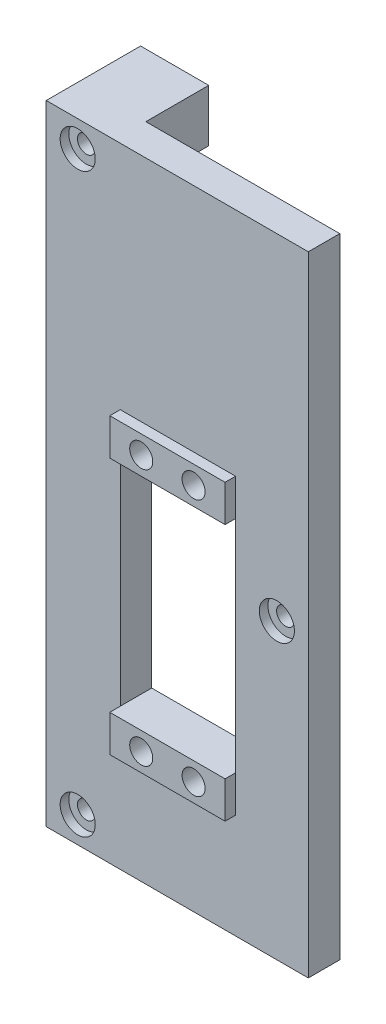
SolidWorks part; units mm, degrees
ref_plane "Front Plane" through (0, 0, 0) normal (1, 0, 0) x (0, 1, 0)
ref_plane "Top Plane" through (0, 0, 0) normal (0, 0, 1) x (0, 1, 0)
ref_plane "Right Plane" through (0, 0, 0) normal (0, 1, 0) x (-1, 0, 0)
sketch "Sketch1" plane through (0, 0, 0) normal (0, 0, 1) x (0, 1, 0)
  line L1 (60, -25) -> (-60, -25)
  line L2 (60, -25) -> (60, 25)
  line L3 (60, 25) -> (-60, 25)
  line L4 (-60, -25) -> (-60, 25)
  line L5 (60, -25) -> (-60, 25) construction
  line L6 (60, 25) -> (-60, -25) construction
  point P0 (0, 0)
  dimension "D1" = 120
  dimension "D2" = 50
extrude "Boss-Extrude1" add sketch "Sketch1" along normal blind 6
sketch "Sketch2" plane through (0, 0, 0) normal (0, 0, -1) x (1, 0, 0)
  line L0 (25, 60) -> (25, -60) construction
  line L1 (-25, 60) -> (25, 60)
  line L2 (-25, 60) -> (-25, 50)
  line L3 (-25, 50) -> (25, 50)
  line L4 (25, 60) -> (25, 50)
  line L5 (25, 0) -> (-25, 0) construction
  line L6 (-25, -60) -> (-25, 60) construction
  line L7 (25, -60) -> (25, -50)
  line L8 (-25, -50) -> (25, -50)
  line L9 (-25, -60) -> (-25, -50)
  line L10 (-25, -60) -> (25, -60)
  point P13 (0, 0)
  dimension "D1" = 10
extrude "Boss-Extrude2" add sketch "Sketch2" along normal blind 12
sketch "Sketch3" plane through (0, 0, 6) normal (0, 0, 1) x (1, 0, 0)
  line L0 (25, 0) -> (-25, 0) construction
  line L1 (-25, 60) -> (-25, -60) construction
  line L2 (-25, -60) -> (25, -60) construction
  circle A0 centre (-19, -55) radius 1.7
  circle A3 centre (-19, 55) radius 1.7
  point P10 (0, 0)
  dimension "D1" = 3.4
  dimension "D3" = 6
  dimension "D5" = 5
extrude "Cut-Extrude1" cut sketch "Sketch3" against normal blind 19
sketch "Sketch5" plane through (25, 0, 0) normal (1, 0, 0) x (0, 1, 0)
  line L0 (0, 0) -> (0, -11.428) construction
  line L2 (-50, 0) -> (-60, 0)
  line L3 (-50, 0) -> (-50, -12)
  line L4 (-50, -12) -> (-60, -12)
  line L5 (-60, 0) -> (-60, -12)
  line L6 (50, 0) -> (60, 0)
  line L7 (50, 0) -> (50, -12)
  line L8 (50, -12) -> (60, -12)
  line L9 (60, 0) -> (60, -12)
extrude "Cut-Extrude2" cut sketch "Sketch5" against normal blind 37
sketch "Sketch6" plane through (0, 0, 0) normal (0, 0, -1) x (1, 0, 0)
  line L0 (25, 60) -> (25, -60) construction
  line L1 (-12, 60) -> (25, 60) construction
  circle A0 centre (19, 4) radius 1.7
  dimension "D1" = 3.4
  dimension "D2" = 6
  dimension "D3" = 56
hole_wizard "CBORE for M3 SBHCS2" positions "3DSketch2" profile "Sketch7" counterbore size "M3" standard "ANSI Metric"
sketch3d "3DSketch2"
  line L0 (-19, 55, -12) -> (-19, 55, 6) construction
  line L1 (-19, -55, -12) -> (-19, -55, 6) construction
  point P0 (-19, 55, 6)
  point P4 (-19, -55, 6)
sketch "Sketch7" plane through (-19, 55, 6) normal (1, 0, 0) x (0, -1, 0)
  line L0 (0, 0) -> (0, 4.1715)
  line L1 (0, 4.1715) -> (1.7, 3.15)
  line L2 (1.7, 3.15) -> (1.7, 1.65)
  line L3 (1.7, 1.65) -> (3.35, 1.65)
  line L4 (3.35, 1.65) -> (3.35, 0)
  line L5 (3.35, 0) -> (0, 0)
  line L10 (0, 4.1715) -> (-1.7, 3.15) construction
  line L11 (0, -6.35) -> (0, 107.95) construction
  dimension "Hole Dia." = 3.4
  dimension "Hole Depth" = 3.15
  dimension "C'Bore Dia." = 6.7
  dimension "C'Bore Depth" = 1.65
  dimension "Drill Angle" = 118
extrude "Cut-Extrude3" cut sketch "Sketch6" against normal blind 6
hole_wizard "CBORE for M3 SBHCS3" positions "3DSketch3" profile "Sketch8" counterbore size "M3" standard "ANSI Metric"
sketch3d "3DSketch3"
  line L0 (19, -4, 6) -> (19, -4, 0) construction
  point P0 (19, -4, 6)
sketch "Sketch8" plane through (19, -4, 6) normal (1, 0, 0) x (0, -1, 0)
  line L0 (0, 0) -> (0, 4.1715)
  line L1 (0, 4.1715) -> (1.7, 3.15)
  line L2 (1.7, 3.15) -> (1.7, 1.65)
  line L3 (1.7, 1.65) -> (3.35, 1.65)
  line L4 (3.35, 1.65) -> (3.35, 0)
  line L5 (3.35, 0) -> (0, 0)
  line L10 (0, 4.1715) -> (-1.7, 3.15) construction
  line L11 (0, -6.35) -> (0, 107.95) construction
  dimension "Hole Dia." = 3.4
  dimension "Hole Depth" = 3.15
  dimension "C'Bore Dia." = 6.7
  dimension "C'Bore Depth" = 1.65
  dimension "Drill Angle" = 118
sketch "Sketch9" plane through (0, 0, 6) normal (0, 0, 1) x (1, 0, 0)
  line L0 (25, -60) -> (25, 60) construction
  line L1 (-25, -60) -> (25, -60) construction
  circle A0 centre (0.12, -22.03) radius 3.2
  dimension "D1" = 24.88
  dimension "D2" = 37.97
  dimension "D3" = 6.4
extrude "Cut-Extrude4" cut sketch "Sketch9" against normal blind 7
sketch "Sketch10" plane through (0, 0, 6) normal (0, 0, 1) x (1, 0, 0)
  line L1 (-10.88, 8.97) -> (11.12, 8.97)
  line L2 (-10.88, 8.97) -> (-10.88, -33.03)
  line L3 (-10.88, -33.03) -> (11.12, -33.03)
  line L4 (11.12, 8.97) -> (11.12, -33.03)
  circle A0 centre (0.12, -22.03) radius 3.2 construction
  dimension "D1" = 22
  dimension "D2" = 42
  dimension "D3" = 11
  dimension "D4" = 11
extrude "Cut-Extrude5" cut sketch "Sketch10" against normal blind 6.5
sketch "Sketch11" plane through (0, 0, 6) normal (0, 0, 1) x (1, 0, 0)
  line L0 (-10.88, -12.03) -> (11.12, -12.03) construction
  line L1 (-10.88, -33.03) -> (11.12, -33.03)
  line L2 (-10.88, -33.03) -> (-10.88, -40.03)
  line L3 (-10.88, -40.03) -> (11.12, -40.03)
  line L4 (11.12, -33.03) -> (11.12, -40.03)
  line L5 (-10.88, 8.97) -> (-10.88, -33.03) construction
  line L6 (11.12, -33.03) -> (11.12, 8.97) construction
  line L7 (11.12, 8.97) -> (11.12, 15.97)
  line L8 (-10.88, 15.97) -> (11.12, 15.97)
  line L9 (-10.88, 8.97) -> (-10.88, 15.97)
  line L10 (-10.88, 8.97) -> (11.12, 8.97)
  circle A0 centre (-4.88, -36.53) radius 2.2
  circle A1 centre (5.12, -36.53) radius 2.2
  circle A2 centre (5.12, 12.47) radius 2.2
  circle A3 centre (-4.88, 12.47) radius 2.2
  dimension "D3" = 6
  dimension "D5" = 4.4
  dimension "D6" = 4.4
  dimension "D7" = 3.5
  dimension "D8" = 3.5
  dimension "D1" = 7
  dimension "D2" = 22
  dimension "D4" = 6
extrude "Boss-Extrude4" add sketch "Sketch11" along normal blind 2
sketch "Sketch12" plane through (0, 0, 6) normal (0, 0, 1) x (1, 0, 0)
  circle A0 centre (-4.88, -36.53) radius 2.2
  circle A1 centre (5.12, -36.53) radius 2.2
  circle A2 centre (-4.88, 12.47) radius 2.2
  circle A3 centre (5.12, 12.47) radius 2.2
  dimension "D1" = 4.4
  dimension "D2" = 4.4
  dimension "D3" = 4.4
  dimension "D4" = 4.4
extrude "Cut-Extrude6" cut sketch "Sketch12" against normal blind 6
